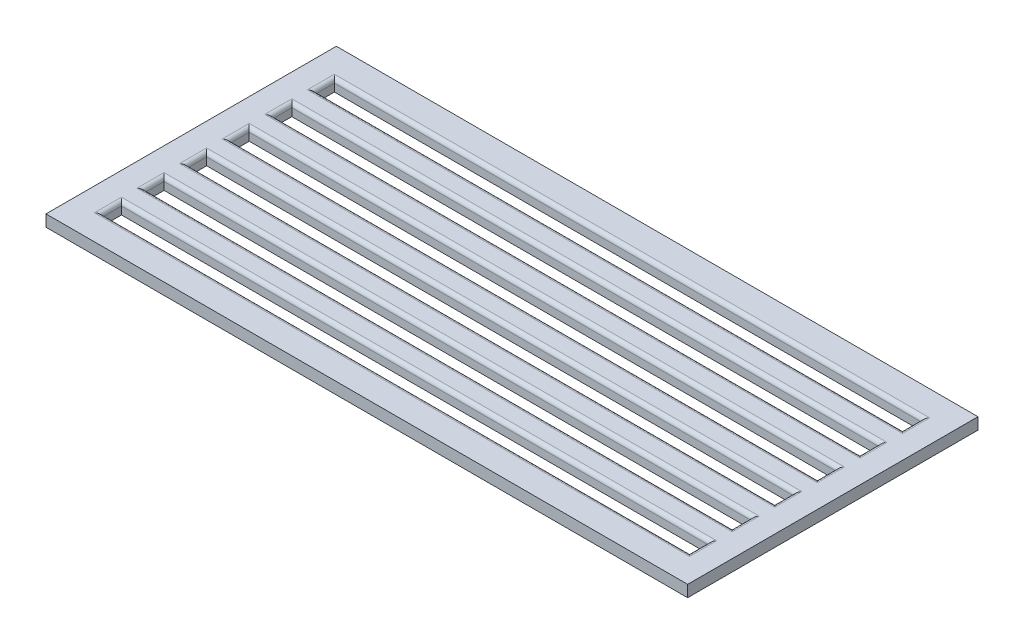
SolidWorks part; units mm, degrees
ref_plane "Front Plane" through (0, 0, 0) normal (0, 0, 1) x (1, 0, 0)
ref_plane "Top Plane" through (0, 0, 0) normal (0, 1, 0) x (1, 0, 0)
ref_plane "Right Plane" through (0, 0, 0) normal (1, 0, 0) x (0, 0, -1)
sketch "Sketch1" plane through (0, 0, 0) normal (0, 1, 0) x (1, 0, 0)
  line L1 (-164.7528, 3.8933) -> (0.9972, 3.8933)
  line L2 (-164.7528, 3.8933) -> (-164.7528, 78.8933)
  line L3 (-164.7528, 78.8933) -> (0.9972, 78.8933)
  line L4 (0.9972, 3.8933) -> (0.9972, 78.8933)
  dimension "D1" = 75
  dimension "D2" = 165.75
extrude "Boss-Extrude1" add sketch "Sketch1" along normal blind 3
sketch "Sketch2" plane through (0, 3, 0) normal (0, 1, 0) x (1, 0, 0)
  line L1 (-157.7528, 71.3933) -> (-6.0028, 71.3933)
  line L2 (-157.7528, 71.3933) -> (-157.7528, 66.3933)
  line L3 (-157.7528, 66.3933) -> (-6.0028, 66.3933)
  line L4 (-6.0028, 71.3933) -> (-6.0028, 66.3933)
  line L5 (-157.7528, 60.3933) -> (-6.0028, 60.3933)
  line L6 (-157.7528, 60.3933) -> (-157.7528, 55.3933)
  line L7 (-157.7528, 55.3933) -> (-6.0028, 55.3933)
  line L8 (-6.0028, 60.3933) -> (-6.0028, 55.3933)
  line L9 (-157.7528, 49.3933) -> (-6.0028, 49.3933)
  line L10 (-157.7528, 49.3933) -> (-157.7528, 44.3933)
  line L11 (-157.7528, 44.3933) -> (-6.0028, 44.3933)
  line L12 (-6.0028, 49.3933) -> (-6.0028, 44.3933)
  line L13 (-157.7528, 38.3933) -> (-6.0028, 38.3933)
  line L14 (-157.7528, 38.3933) -> (-157.7528, 33.3933)
  line L15 (-157.7528, 33.3933) -> (-6.0028, 33.3933)
  line L16 (-6.0028, 38.3933) -> (-6.0028, 33.3933)
  line L17 (-157.7528, 27.3933) -> (-6.0028, 27.3933)
  line L18 (-157.7528, 27.3933) -> (-157.7528, 22.3933)
  line L19 (-157.7528, 22.3933) -> (-6.0028, 22.3933)
  line L20 (-6.0028, 27.3933) -> (-6.0028, 22.3933)
  line L21 (-157.7528, 16.3933) -> (-6.0028, 16.3933)
  line L22 (-157.7528, 16.3933) -> (-157.7528, 11.3933)
  line L23 (-157.7528, 11.3933) -> (-6.0028, 11.3933)
  line L24 (-6.0028, 16.3933) -> (-6.0028, 11.3933)
extrude "Cut-Extrude1" cut sketch "Sketch2" against normal through all contours L2 L1 L4 L3 | L6 L5 L8 L7 | L10 L9 L12 L11 | L14 L13 L16 L15 | L18 L17 L20 L19 | L22 L21 L24 L23
fillet "Fillet4" radius 1 1 edges at (-81.8778, 3, -60.3933)
fillet "Fillet5" radius 1 1 edges at (-81.8778, 3, -66.3933)
fillet "Fillet6" radius 1 1 edges at (-81.8778, 3, -49.3933)
fillet "Fillet7" radius 1 1 edges at (-81.8778, 3, -55.3933)
fillet "Fillet8" radius 1 1 edges at (-81.8778, 3, -38.3933)
fillet "Fillet9" radius 1 1 edges at (-81.8778, 3, -44.3933)
fillet "Fillet10" radius 1 1 edges at (-81.8778, 3, -33.3933)
fillet "Fillet11" radius 1 1 edges at (-81.8778, 3, -27.3933)
fillet "Fillet12" radius 1 1 edges at (-81.8778, 3, -22.3933)
fillet "Fillet13" radius 1 1 edges at (-81.8778, 3, -16.3933)
fillet "Fillet14" radius 1 1 edges at (-81.8778, 3, -11.3933)
fillet "Fillet15" radius 1 1 edges at (-81.8778, 3, -71.3933)
fillet "Fillet16" radius 1 1 edges at (-157.7528, 3, -68.8933)
fillet "Fillet17" radius 1 1 edges at (-157.7528, 3, -57.8933)
fillet "Fillet18" radius 1 1 edges at (-157.7528, 3, -46.8933)
fillet "Fillet19" radius 1 1 edges at (-157.7528, 3, -35.8933)
fillet "Fillet20" radius 1 1 edges at (-157.7528, 3, -24.8933)
fillet "Fillet21" radius 1 1 edges at (-157.7528, 3, -13.8933)
fillet "Fillet22" radius 1 1 edges at (-6.0028, 3, -13.8933)
fillet "Fillet23" radius 1 1 edges at (-6.0028, 3, -24.8933)
fillet "Fillet24" radius 1 1 edges at (-6.0028, 3, -35.8933)
fillet "Fillet25" radius 1 1 edges at (-6.0028, 3, -46.8933)
fillet "Fillet26" radius 1 1 edges at (-6.0028, 3, -57.8933)
fillet "Fillet27" radius 1 1 edges at (-6.0028, 3, -68.8933)
